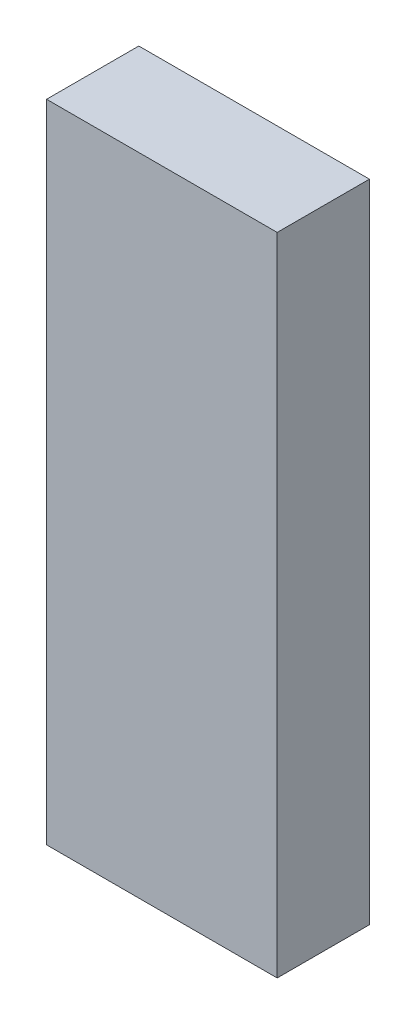
SolidWorks part; units mm, degrees
ref_plane "Front Plane" through (0, 0, 0) normal (0, 0, 1) x (1, 0, 0)
ref_plane "Top Plane" through (0, 0, 0) normal (0, 1, 0) x (1, 0, 0)
ref_plane "Right Plane" through (0, 0, 0) normal (1, 0, 0) x (0, 0, -1)
sketch "Sketch1" plane through (0, 0, 0) normal (0, 0, 1) x (1, 0, 0)
  line L0 (3850, 580) -> (3850, 720)
  line L1 (3850, 720) -> (3900, 720)
  line L2 (3900, 720) -> (3900, 580)
  line L3 (3900, 580) -> (3850, 580)
extrude "Boss-Extrude1" add sketch "Sketch1" along normal blind 20
